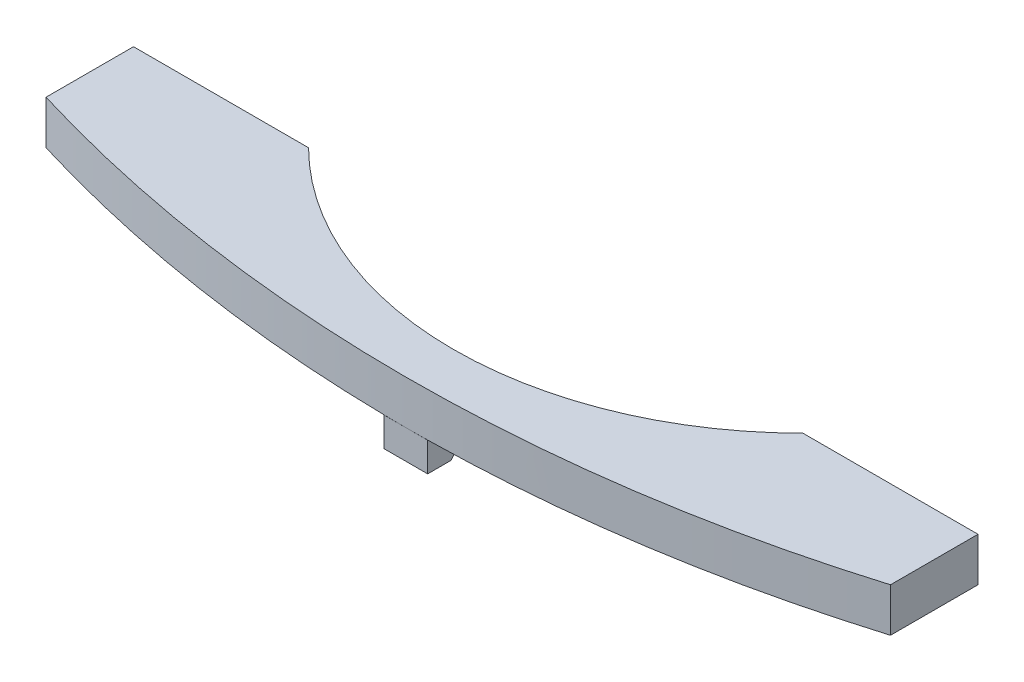
SolidWorks part; units mm, degrees
ref_plane "Front Plane" through (0, 0, 0) normal (0, 0, 1) x (1, 0, 0)
ref_plane "Top Plane" through (0, 0, 0) normal (0, 1, 0) x (1, 0, 0)
ref_plane "Right Plane" through (0, 0, 0) normal (1, 0, 0) x (0, 0, -1)
sketch "Sketch1" plane through (0, 0, 0) normal (0, 1, 0) x (1, 0, 0)
  line L0 (0, 0) -> (0, -19.05)
  line L1 (183.8325, 0) -> (183.8325, -19.05)
  line L2 (0, 0) -> (38.1, 0)
  line L3 (183.8325, 0) -> (145.7325, 0)
  arc A1 (0, -19.05) -> (183.8325, -19.05) centre (91.9163, 284.854) ccw
  arc A2 (38.1, 0) -> (145.7325, 0) centre (91.9162, 53.9467) ccw
  dimension "D6" = 76.2
  dimension "D7" = 317.5
  dimension "D1" = 183.8325
  dimension "D2" = 38.1
  dimension "D3" = 38.1
  dimension "D4" = 19.05
  dimension "D5" = 19.05
extrude "Boss-Extrude1" add sketch "Sketch1" along normal blind 9.525
ref_plane "Plane1" through (91.9163, 0, 0) normal (1, 0, 0) x (0, 0, -1)
sketch "Sketch2" plane through (91.9163, 0, 0) normal (1, 0, 0) x (0, 0, -1)
  line L6 (-32.646, 0) -> (-32.646, -6.35)
  line L7 (-32.646, 0) -> (-19.05, 0) construction
  line L8 (-32.646, -6.35) -> (-27.5815, -6.35)
  line L9 (-27.5815, -6.35) -> (-22.2533, 0)
  line L10 (-22.2533, 0) -> (-32.646, 0)
  dimension "D1" = 6.35
  dimension "D2" = 50
extrude "Boss-Extrude2" add sketch "Sketch2" along normal mid plane 9.525
